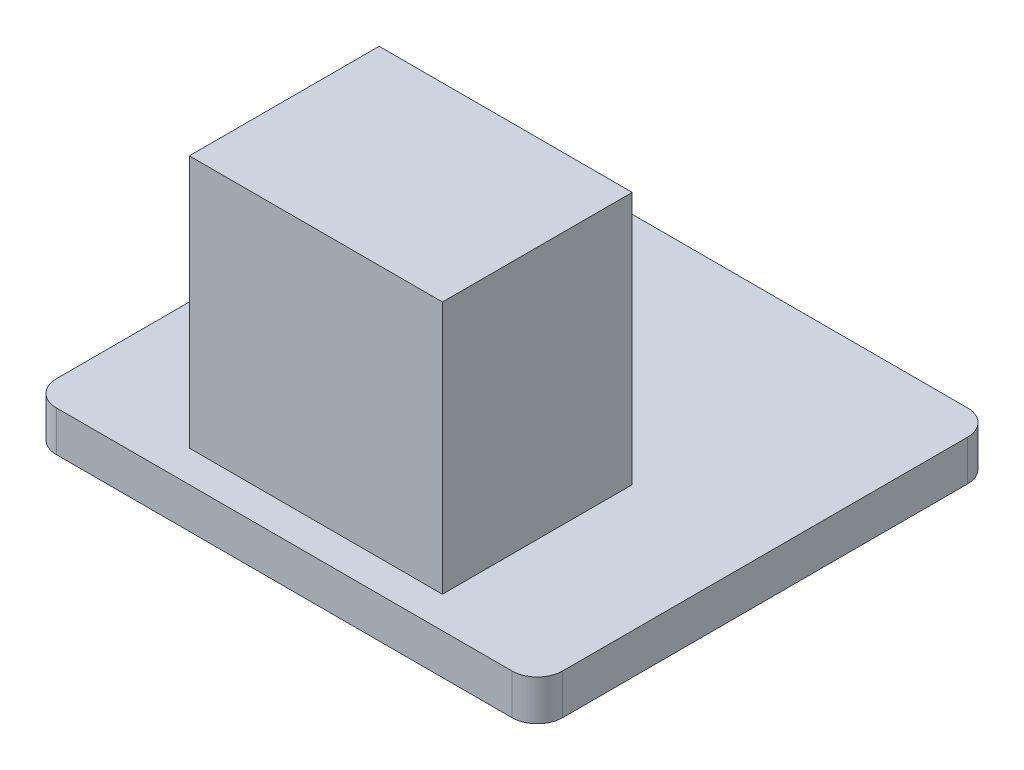
SolidWorks part; units mm, degrees
ref_plane "Front Plane" through (0, 0, 0) normal (0, 0, 1) x (1, 0, 0)
ref_plane "Top Plane" through (0, 0, 0) normal (0, 1, 0) x (1, 0, 0)
ref_plane "Right Plane" through (0, 0, 0) normal (1, 0, 0) x (0, 0, -1)
sketch "Sketch1" plane through (0, 0, 0) normal (0, 1, 0) x (1, 0, 0)
  line L0 (-56, -21) -> (-38, -21)
  line L1 (-37, -22) -> (-37, -38)
  line L2 (-38, -39) -> (-56, -39)
  line L3 (-57, -38) -> (-57, -22)
  arc A0 (-57, -22) -> (-56, -21) centre (-56, -22) cw
  arc A1 (-38, -21) -> (-37, -22) centre (-38, -22) cw
  arc A2 (-37, -38) -> (-38, -39) centre (-38, -38) cw
  arc A3 (-56, -39) -> (-57, -38) centre (-56, -38) cw
extrude "Board" add sketch "Sketch1" along normal blind 1.6 from offset 10
sketch "Sketch2" plane through (0, 0, 0) normal (0, 1, 0) x (1, 0, 0)
  line L0 (-52, -30.25) -> (-42, -30.25)
  line L1 (-42, -30.25) -> (-42, -37.75)
  line L2 (-42, -37.75) -> (-52, -37.75)
  line L3 (-52, -37.75) -> (-52, -30.25)
extrude "Terminal" add sketch "Sketch2" along normal blind 10 from offset 11.6
